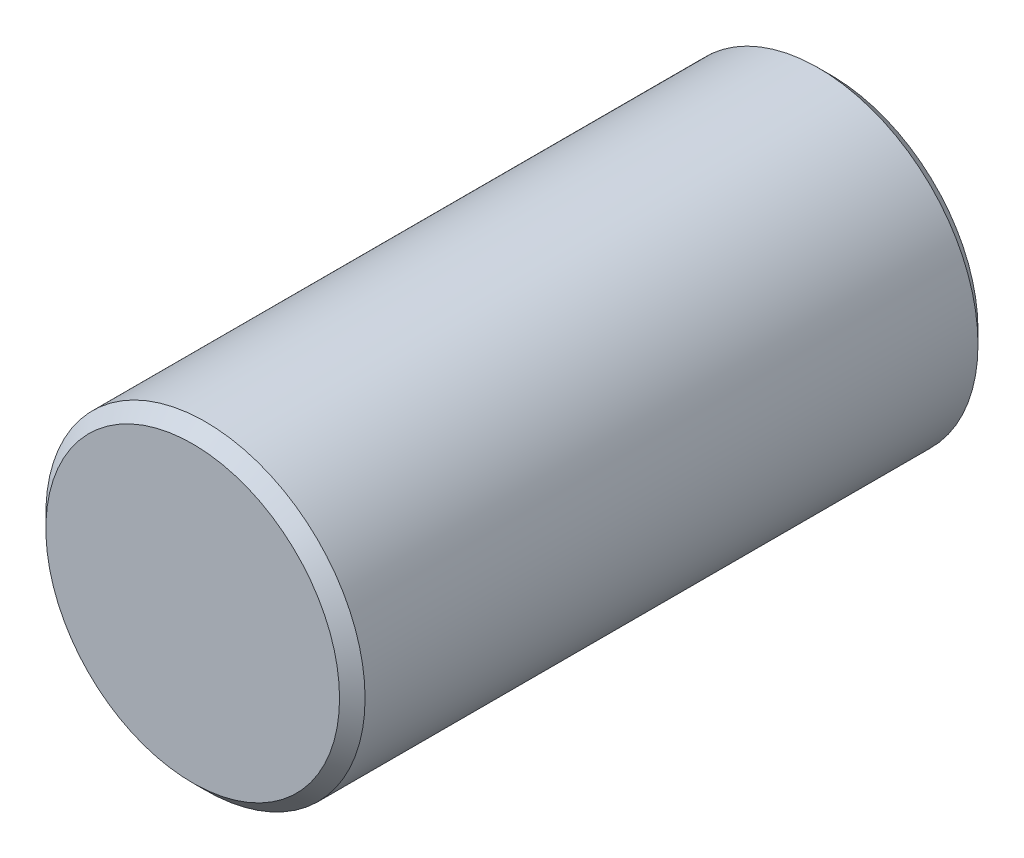
SolidWorks part; units mm, degrees
material "Cast Alloy Steel"
ref_plane "Front" through (0, 0, 0) normal (0, 0, 1) x (1, 0, 0)
ref_plane "Top" through (0, 0, 0) normal (0, 1, 0) x (1, 0, 0)
ref_plane "Right" through (0, 0, 0) normal (1, 0, 0) x (0, 0, -1)
sketch "Sketch1" plane through (0, 0, 0) normal (0, 0, 1) x (1, 0, 0)
  circle A0 centre (0, 0) radius 50
  dimension "D1" = 100
extrude "Boss-Extrude1" add sketch "Sketch1" along normal blind 200
chamfer "Chamfer1" distance 4 angle 45 2 edges at (50, 0, 200) (50, 0, 0)
scale "Echelle1" bodies to scale 101 scale about centroid uniform scaling yes scale factor 0.075
